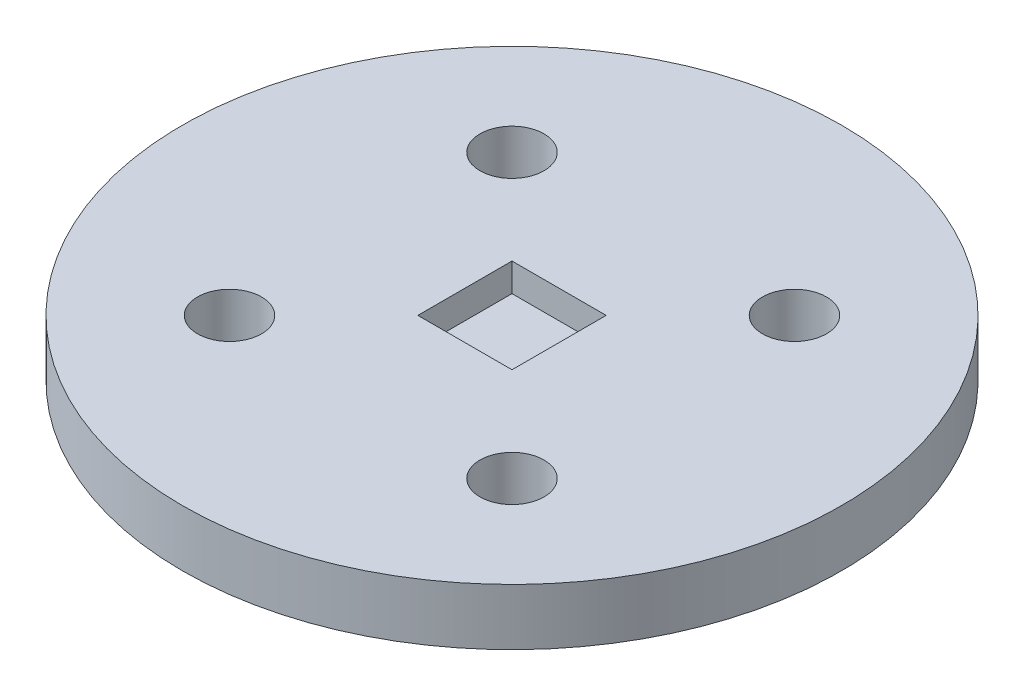
SolidWorks part; units mm, degrees
ref_plane "Front Plane" through (0, 0, 0) normal (0, 0, 1) x (1, 0, 0)
ref_plane "Top Plane" through (0, 0, 0) normal (0, 1, 0) x (1, 0, 0)
ref_plane "Right Plane" through (0, 0, 0) normal (1, 0, 0) x (0, 0, -1)
sketch "Sketch1" plane through (0, 0, 0) normal (0, 1, 0) x (1, 0, 0)
  circle A0 centre (0, 0) radius 35
  dimension "D1" = 70
extrude "Boss-Extrude1" add sketch "Sketch1" along normal blind 6
sketch "Sketch6" plane through (0, 0, -4.1325) normal (0, -1, 0) x (1, 0, 0)
  line L0 (35, 4.1325) -> (-35, 4.1325) construction
  line L5 (-26.1992, 1.036) -> (-26.1992, 7.236)
  line L6 (-19.9992, 7.236) -> (-26.1992, 7.236)
  line L11 (-19.9992, 1.036) -> (-19.9992, 7.236)
  line L12 (-19.9992, 1.036) -> (-26.1992, 1.036)
  line L13 (-3.0965, 24.1316) -> (3.1035, 24.1316)
  line L14 (-3.0965, 24.1316) -> (-3.0965, 30.3316)
  line L15 (-3.0965, 30.3316) -> (3.1035, 30.3316)
  line L16 (3.1035, 24.1316) -> (3.1035, 30.3316)
  line L17 (-3.0965, 24.1316) -> (3.1035, 30.3316) construction
  line L18 (-3.0965, 30.3316) -> (3.1035, 24.1316) construction
  line L19 (3.0965, -22.0667) -> (-3.1035, -22.0667)
  line L20 (-3.1035, -15.8667) -> (-3.1035, -22.0667)
  line L21 (3.0965, -15.8667) -> (-3.1035, -15.8667)
  line L22 (3.0965, -15.8667) -> (3.0965, -22.0667)
  line L23 (26.1992, 7.2289) -> (26.1992, 1.0289)
  line L24 (19.9992, 1.0289) -> (26.1992, 1.0289)
  line L25 (19.9992, 7.2289) -> (19.9992, 1.0289)
  line L26 (19.9992, 7.2289) -> (26.1992, 7.2289)
  circle A0 centre (0, 4.1325) radius 35 construction
  point P0 (-0.0024, 27.1982)
  point P5 (-0.0024, 27.1982)
  dimension "D1" = 4
  dimension "D6" = 6.2
  dimension "D7" = 6.2
sketch "Sketch11" plane through (0, 6, 0) normal (0, 1, 0) x (1, 0, 0)
  line L1 (-5, -5) -> (5, -5)
  line L2 (-5, -5) -> (-5, 5)
  line L3 (-5, 5) -> (5, 5)
  line L4 (5, -5) -> (5, 5)
  line L5 (-5, -5) -> (5, 5) construction
  line L6 (-5, 5) -> (5, -5) construction
  point P0 (0, 0)
  dimension "D1" = 10
  dimension "D2" = 10
extrude "Cut-Extrude3" cut sketch "Sketch11" against normal blind 3
sketch "Sketch12" plane through (0, 0, 0) normal (0, -1, 0) x (1, 0, 0)
  circle A1 centre (15, -15) radius 3.4
  circle A2 centre (-15, -15) radius 3.4
  circle A3 centre (15, 15) radius 3.4
  circle A4 centre (-15, 15) radius 3.4
  point P0 (0, 0)
  point P20 (0, 0)
  dimension "D2" = 6.8
  dimension "D3" = 6.8
  dimension "D4" = 6.8
  dimension "D5" = 6.8
extrude "Cut-Extrude4" cut sketch "Sketch12" against normal through all
extrude "Cut-Extrude6" cut sketch "Sketch6" against normal blind 1.5
